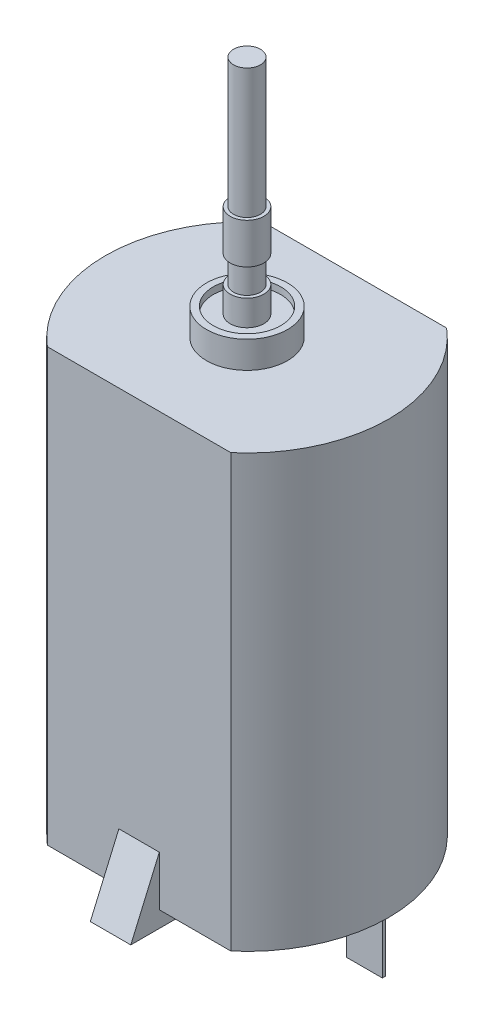
SolidWorks part; units mm, degrees
ref_plane "前视基准面" through (0, 0, 0) normal (0, 0, 1) x (1, 0, 0)
ref_plane "上视基准面" through (0, 0, 0) normal (0, 1, 0) x (1, 0, 0)
ref_plane "右视基准面" through (0, 0, 0) normal (1, 0, 0) x (0, 0, -1)
other "Configuration Table"
sketch "草图1" plane through (0, 0, 0) normal (0, 1, 0) x (1, 0, 0)
  line L1 (-10.5, -8) -> (10.5, -8)
  line L2 (-10.5, -8) -> (-10.5, 8)
  line L3 (-10.5, 8) -> (10.5, 8)
  line L4 (10.5, -8) -> (10.5, 8)
  line L5 (-10.5, -8) -> (10.5, 8) construction
  line L6 (-10.5, 8) -> (10.5, -8) construction
  point P0 (0, 0)
  dimension "D1" = 16
  dimension "D2" = 21
extrude "凸台-拉伸1" add sketch "草图1" along normal blind 32
sketch "草图2" plane through (0, 0, 0) normal (0, -1, 0) x (1, 0, 0)
  circle A0 centre (0, 0) radius 3
  dimension "6" = 6
extrude "凸台-拉伸2" add sketch "草图2" along normal blind 2
sketch "草图3" plane through (0, 32, 0) normal (0, 1, 0) x (1, 0, 0)
  line L0 (10.5, 8) -> (-10.5, 8) construction
  line L1 (-10.5, -8) -> (10.5, -8) construction
  line L4 (10.5, -8) -> (10.5, 8) construction
  line L5 (-10.5, 8) -> (-10.5, -8) construction
  line L6 (-6.8007, 8) -> (-10.5, 8)
  line L7 (-10.5, 8) -> (-10.5, -8)
  line L8 (-10.5, -8) -> (-6.8007, -8)
  line L9 (6.8007, -8) -> (10.5, -8)
  line L10 (10.5, -8) -> (10.5, 8)
  line L11 (10.5, 8) -> (6.8007, 8)
  arc A0 (6.8007, 8) -> (6.8007, -8) centre (0, 0) cw
  arc A1 (-6.8007, 8) -> (-6.8007, -8) centre (0, 0) ccw
  line M1 (10.5, -8) -> (10.5, 8)
  line M2 (10.5, 8) -> (-10.5, 8)
  line M3 (-10.5, 8) -> (-10.5, -8)
  line M4 (-10.5, -8) -> (10.5, -8)
extrude "切除-拉伸1" cut sketch "草图3" against normal through all contours A1 L7 M4 | A0 M1 M4 | A0 L10 M2 | A1 M2 M3
sketch "草图4" plane through (0, 0, 0) normal (0, -1, 0) x (1, 0, 0)
  line L0 (0, 0) -> (0, 50000) construction
  line L1 (-10.1463, -0.1144) -> (-7.4994, -0.1144)
  line L2 (-10.1463, -0.1144) -> (-10.1463, 0.1144)
  line L3 (-10.1463, 0.1144) -> (-7.4994, 0.1144)
  line L4 (-7.4994, -0.1144) -> (-7.4994, 0.1144)
  line L5 (-10.1463, -0.1144) -> (-7.4994, 0.1144) construction
  line L6 (-10.1463, 0.1144) -> (-7.4994, -0.1144) construction
  line L7 (10.1463, 0.1144) -> (7.4994, -0.1144) construction
  line L8 (10.1463, -0.1144) -> (7.4994, 0.1144) construction
  line L9 (7.4994, -0.1144) -> (7.4994, 0.1144)
  line L10 (10.1463, 0.1144) -> (7.4994, 0.1144)
  line L11 (10.1463, -0.1144) -> (10.1463, 0.1144)
  line L12 (10.1463, -0.1144) -> (7.4994, -0.1144)
  point P0 (-8.8229, 0)
  point P12 (8.8229, 0)
extrude "凸台-拉伸3" add sketch "草图4" along normal blind 4
sketch "草图5" plane through (0, 32, 0) normal (0, 1, 0) x (1, 0, 0)
  circle A0 centre (0, 0) radius 3
  dimension "D1" = 6
extrude "凸台-拉伸4" add sketch "草图5" along normal blind 2
sketch "草图6" plane through (0, 34, 0) normal (0, 1, 0) x (1, 0, 0)
  circle A2 centre (0, 0) radius 2.5
  circle A3 centre (0, 0) radius 2.5
  dimension "D1" = 0.5
extrude "切除-拉伸2" cut sketch "草图6" against normal blind 0.5
sketch "草图7" plane through (0, 33.5, 0) normal (0, 1, 0) x (1, 0, 0)
  circle A0 centre (0, 0) radius 1
  dimension "D1" = 2
extrude "凸台-拉伸5" add sketch "草图7" along normal blind 16.5
sketch "草图8" plane through (0, 33.5, 0) normal (0, 1, 0) x (1, 0, 0)
  circle A0 centre (0, 0) radius 1
  circle A1 centre (0, 0) radius 1.25
  circle M1 centre (0, 0) radius 1
  dimension "D1" = 2.5
extrude "凸台-拉伸6" add sketch "草图8" along a picked direction on the side of the normal blind 1.9 contours A1 M1 | A0
ref_plane "基准面1" through (0, 37.4, 0) normal (0, 1, 0) x (1, 0, 0)
sketch "草图9" plane through (0, 37.4, 0) normal (0, 1, 0) x (1, 0, 0)
  circle A0 centre (0, 0) radius 1
  circle A1 centre (0, 0) radius 1.25
extrude "凸台-拉伸7" add sketch "草图9" along normal up to surface (3 mm away)
sketch "草图11" plane through (0, 0, 0) normal (1, 0, 0) x (0, 0, -1)
  line L0 (0, 0) -> (0, 50000) construction
  line L1 (8, 3.6972) -> (10.1149, -1.2)
  line L2 (8, 32) -> (8, 0) construction
  line L3 (-12, -1.2) -> (37, -1.2) construction
  line L4 (10.1149, -1.2) -> (6.553, -1.2)
  line L5 (6.553, -1.2) -> (6.553, 0)
  line L6 (-8, 0) -> (8, 0) construction
  line L7 (6.553, 0) -> (8, 0)
  line L8 (8, 0) -> (8, 3.6972)
  line L9 (-8, 0) -> (-8, 3.6972)
  line L10 (-6.553, 0) -> (-8, 0)
  line L11 (-6.553, -1.2) -> (-6.553, 0)
  line L12 (-10.1149, -1.2) -> (-6.553, -1.2)
  line L13 (-8, 3.6972) -> (-10.1149, -1.2)
extrude "凸台-拉伸8" add sketch "草图11" along normal mid plane 3 separate body
